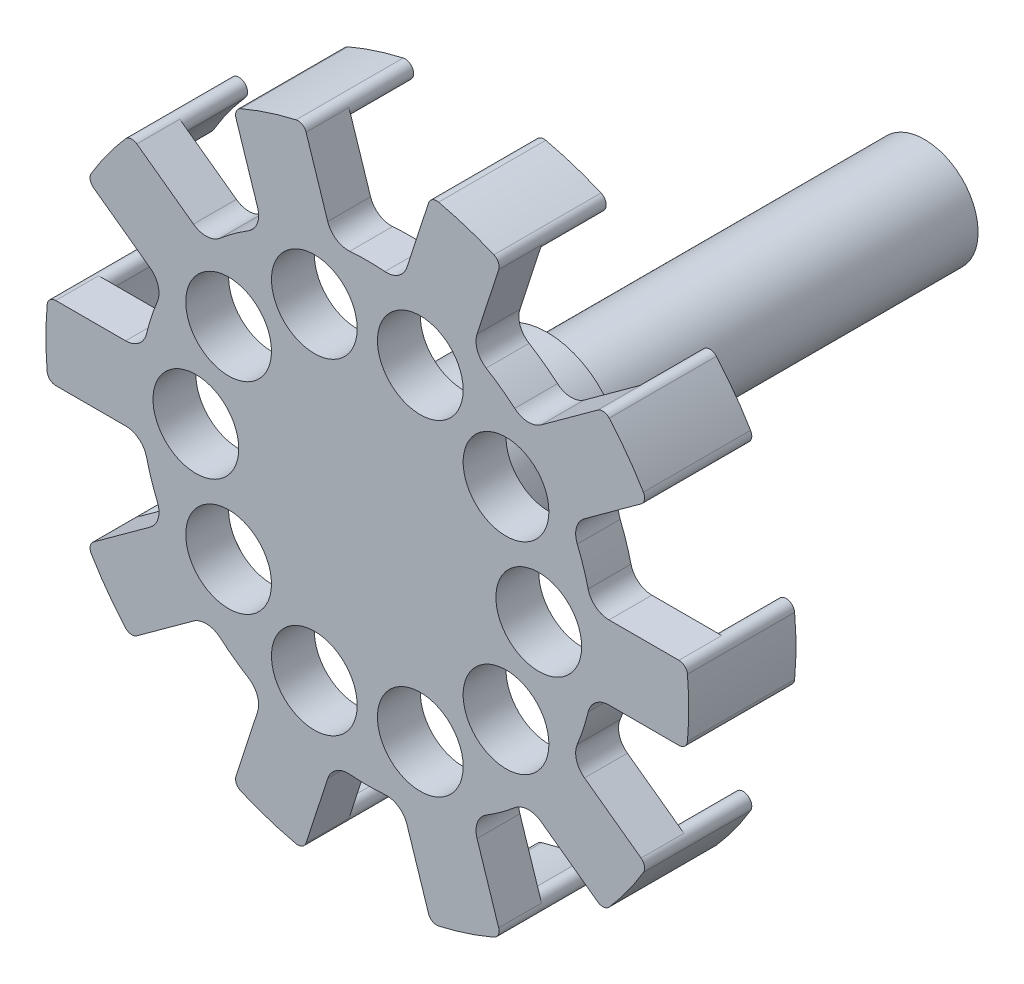
SolidWorks part; units mm, degrees
ref_plane "Piano frontale" through (0, 0, 0) normal (0, 0, 1) x (1, 0, 0)
ref_plane "Piano superiore" through (0, 0, 0) normal (0, 1, 0) x (1, 0, 0)
ref_plane "Piano destro" through (0, 0, 0) normal (1, 0, 0) x (0, 0, -1)
sketch "Schizzo1" plane through (0, 0, 0) normal (0, 0, 1) x (1, 0, 0)
  line L0 (-40, 0) -> (40, 0) construction
  circle A0 centre (0, 0) radius 53
  circle A1 centre (0, 0) radius 40 construction
  circle A2 centre (40, 0) radius 10
  circle A3 centre (0, 0) radius 40 construction
  circle A4 centre (32.3607, -23.5114) radius 10
  circle A5 centre (0, 0) radius 40 construction
  circle A6 centre (12.3607, -38.0423) radius 10
  circle A7 centre (0, 0) radius 40 construction
  circle A8 centre (-12.3607, -38.0423) radius 10
  circle A9 centre (0, 0) radius 40 construction
  circle A10 centre (-32.3607, -23.5114) radius 10
  circle A11 centre (0, 0) radius 40 construction
  circle A12 centre (-40, 0) radius 10
  circle A13 centre (0, 0) radius 40 construction
  circle A14 centre (-32.3607, 23.5114) radius 10
  circle A15 centre (0, 0) radius 40 construction
  circle A16 centre (-12.3607, 38.0423) radius 10
  circle A17 centre (0, 0) radius 40 construction
  circle A18 centre (12.3607, 38.0423) radius 10
  circle A19 centre (0, 0) radius 40 construction
  circle A20 centre (32.3607, 23.5114) radius 10
  dimension "D1" = 106
  dimension "D2" = 80
  dimension "D3" = 20
  dimension "D4" = 10
extrude "Estrusione-Estrusione1" add sketch "Schizzo1" along normal blind 10
sketch "Schizzo2" plane through (0, 0, 0) normal (0, 0, -1) x (-1, 0, 0)
  line L0 (0, 0) -> (117.2597, 0) construction
  line L1 (52.2976, 8.6) -> (72.701, 8.6)
  line L2 (52.2976, -8.6) -> (72.701, -8.6)
  line L3 (47.3646, -23.7822) -> (63.8713, -35.775)
  line L4 (37.2547, -37.6973) -> (53.7614, -49.6901)
  line L5 (24.3399, -47.0804) -> (30.6449, -66.4852)
  line L6 (7.9818, -52.3955) -> (14.2868, -71.8003)
  line L7 (-7.9818, -52.3955) -> (-14.2868, -71.8003)
  line L8 (-24.3399, -47.0804) -> (-30.6449, -66.4852)
  line L9 (-37.2547, -37.6973) -> (-53.7614, -49.6901)
  line L10 (-47.3646, -23.7822) -> (-63.8713, -35.775)
  line L11 (-52.2976, -8.6) -> (-72.701, -8.6)
  line L12 (-52.2976, 8.6) -> (-72.701, 8.6)
  line L13 (-47.3646, 23.7822) -> (-63.8713, 35.775)
  line L14 (-37.2547, 37.6973) -> (-53.7614, 49.6901)
  line L15 (-24.3399, 47.0804) -> (-30.6449, 66.4852)
  line L16 (-7.9818, 52.3955) -> (-14.2868, 71.8003)
  line L17 (7.9818, 52.3955) -> (14.2868, 71.8003)
  line L18 (24.3399, 47.0804) -> (30.6449, 66.4852)
  line L19 (37.2547, 37.6973) -> (53.7614, 49.6901)
  line L20 (47.3646, 23.7822) -> (63.8713, 35.775)
  circle A0 centre (0, 0) radius 53 construction
  arc A1 (64.4134, -38.4176) -> (56.4421, -49.3892) centre (0, 0) cw
  arc A2 (74.6928, 6.7808) -> (74.6928, -6.7808) centre (0, 0) cw
  arc A3 (74.6928, 6.7808) -> (72.701, 8.6) centre (72.701, 6.6) ccw
  arc A4 (74.6928, -6.7808) -> (72.701, -8.6) centre (72.701, -6.6) cw
  arc A5 (64.4134, -38.4176) -> (63.8713, -35.775) centre (62.6958, -37.3931) ccw
  arc A6 (56.4421, -49.3892) -> (53.7614, -49.6901) centre (54.937, -48.0721) cw
  arc A7 (29.5303, -68.9417) -> (16.6324, -73.1325) centre (0, 0) cw
  arc A8 (29.5303, -68.9417) -> (30.6449, -66.4852) centre (28.7428, -67.1033) ccw
  arc A9 (16.6324, -73.1325) -> (14.2868, -71.8003) centre (16.1889, -71.1823) cw
  arc A10 (-16.6324, -73.1325) -> (-29.5303, -68.9417) centre (0, 0) cw
  arc A11 (-16.6324, -73.1325) -> (-14.2868, -71.8003) centre (-16.1889, -71.1823) ccw
  arc A12 (-29.5303, -68.9417) -> (-30.6449, -66.4852) centre (-28.7428, -67.1033) cw
  arc A13 (-56.4421, -49.3892) -> (-64.4134, -38.4176) centre (0, 0) cw
  arc A14 (-56.4421, -49.3892) -> (-53.7614, -49.6901) centre (-54.937, -48.0721) ccw
  arc A15 (-64.4134, -38.4176) -> (-63.8713, -35.775) centre (-62.6958, -37.3931) cw
  arc A16 (-74.6928, -6.7808) -> (-74.6928, 6.7808) centre (0, 0) cw
  arc A17 (-74.6928, -6.7808) -> (-72.701, -8.6) centre (-72.701, -6.6) ccw
  arc A18 (-74.6928, 6.7808) -> (-72.701, 8.6) centre (-72.701, 6.6) cw
  arc A19 (-64.4134, 38.4176) -> (-56.4421, 49.3892) centre (0, 0) cw
  arc A20 (-64.4134, 38.4176) -> (-63.8713, 35.775) centre (-62.6958, 37.3931) ccw
  arc A21 (-56.4421, 49.3892) -> (-53.7614, 49.6901) centre (-54.937, 48.0721) cw
  arc A22 (-29.5303, 68.9417) -> (-16.6324, 73.1325) centre (0, 0) cw
  arc A23 (-29.5303, 68.9417) -> (-30.6449, 66.4852) centre (-28.7428, 67.1033) ccw
  arc A24 (-16.6324, 73.1325) -> (-14.2868, 71.8003) centre (-16.1889, 71.1823) cw
  arc A25 (16.6324, 73.1325) -> (29.5303, 68.9417) centre (0, 0) cw
  arc A26 (16.6324, 73.1325) -> (14.2868, 71.8003) centre (16.1889, 71.1823) ccw
  arc A27 (29.5303, 68.9417) -> (30.6449, 66.4852) centre (28.7428, 67.1033) cw
  arc A28 (56.4421, 49.3892) -> (64.4134, 38.4176) centre (0, 0) cw
  arc A29 (56.4421, 49.3892) -> (53.7614, 49.6901) centre (54.937, 48.0721) ccw
  arc A30 (64.4134, 38.4176) -> (63.8713, 35.775) centre (62.6958, 37.3931) cw
  arc A31 (-37.2547, 37.6973) -> (-47.3646, 23.7822) centre (0, 0) ccw
  arc A32 (-7.9818, 52.3955) -> (-24.3399, 47.0804) centre (0, 0) ccw
  arc A33 (24.3399, 47.0804) -> (7.9818, 52.3955) centre (0, 0) ccw
  arc A34 (47.3646, 23.7822) -> (37.2547, 37.6973) centre (0, 0) ccw
  arc A35 (52.2976, -8.6) -> (52.2976, 8.6) centre (0, 0) ccw
  arc A36 (37.2547, -37.6973) -> (47.3646, -23.7822) centre (0, 0) ccw
  arc A37 (7.9818, -52.3955) -> (24.3399, -47.0804) centre (0, 0) ccw
  arc A38 (-24.3399, -47.0804) -> (-7.9818, -52.3955) centre (0, 0) ccw
  arc A39 (-47.3646, -23.7822) -> (-37.2547, -37.6973) centre (0, 0) ccw
  arc A40 (-52.2976, 8.6) -> (-52.2976, -8.6) centre (0, 0) ccw
  dimension "D3" = 10
  dimension "D4" = 75
  dimension "D5" = 2
  dimension "D6" = 2
  dimension "D1" = 17.2
  dimension "D2" = 8.6
extrude "Estrusione-Estrusione2" add sketch "Schizzo2" against normal blind 10
sketch "Schizzo3" plane through (0, 0, 0) normal (0, 0, -1) x (-1, 0, 0)
  line L0 (72.701, 8.6) -> (52.2976, 8.6) construction
  line L1 (52.2976, -8.6) -> (72.701, -8.6) construction
  arc A0 (74.6928, -6.7808) -> (74.6928, 6.7808) centre (0, 0) ccw
  arc A1 (-56.4421, 49.3892) -> (-64.4134, 38.4176) centre (0, 0) ccw construction
  arc A2 (70.7092, -6.4192) -> (70.7092, 6.4192) centre (0, 0) ccw
  arc A3 (74.6928, 6.7808) -> (70.7092, 6.4192) centre (72.701, 6.6) ccw
  arc A4 (70.7092, -6.4192) -> (74.6928, -6.7808) centre (72.701, -6.6) ccw
  arc A5 (53.4319, -46.7551) -> (60.9781, -36.3686) centre (0, 0) ccw
  arc A6 (56.4421, -49.3892) -> (64.4134, -38.4176) centre (0, 0) ccw
  arc A7 (64.4134, -38.4176) -> (60.9781, -36.3686) centre (62.6958, -37.3931) ccw
  arc A8 (53.4319, -46.7551) -> (56.4421, -49.3892) centre (54.937, -48.0721) ccw
  arc A9 (15.7454, -69.2321) -> (27.9554, -65.2648) centre (0, 0) ccw
  arc A10 (16.6324, -73.1325) -> (29.5303, -68.9417) centre (0, 0) ccw
  arc A11 (29.5303, -68.9417) -> (27.9554, -65.2648) centre (28.7428, -67.1033) ccw
  arc A12 (15.7454, -69.2321) -> (16.6324, -73.1325) centre (16.1889, -71.1823) ccw
  arc A13 (-27.9554, -65.2648) -> (-15.7454, -69.2321) centre (0, 0) ccw
  arc A14 (-29.5303, -68.9417) -> (-16.6324, -73.1325) centre (0, 0) ccw
  arc A15 (-16.6324, -73.1325) -> (-15.7454, -69.2321) centre (-16.1889, -71.1823) ccw
  arc A16 (-27.9554, -65.2648) -> (-29.5303, -68.9417) centre (-28.7428, -67.1033) ccw
  arc A17 (-60.9781, -36.3686) -> (-53.4319, -46.7551) centre (0, 0) ccw
  arc A18 (-64.4134, -38.4176) -> (-56.4421, -49.3892) centre (0, 0) ccw
  arc A19 (-56.4421, -49.3892) -> (-53.4319, -46.7551) centre (-54.937, -48.0721) ccw
  arc A20 (-60.9781, -36.3686) -> (-64.4134, -38.4176) centre (-62.6958, -37.3931) ccw
  arc A21 (-70.7092, 6.4192) -> (-70.7092, -6.4192) centre (0, 0) ccw
  arc A22 (-74.6928, 6.7808) -> (-74.6928, -6.7808) centre (0, 0) ccw
  arc A23 (-74.6928, -6.7808) -> (-70.7092, -6.4192) centre (-72.701, -6.6) ccw
  arc A24 (-70.7092, 6.4192) -> (-74.6928, 6.7808) centre (-72.701, 6.6) ccw
  arc A25 (-53.4319, 46.7551) -> (-60.9781, 36.3686) centre (0, 0) ccw
  arc A26 (-56.4421, 49.3892) -> (-64.4134, 38.4176) centre (0, 0) ccw
  arc A27 (-64.4134, 38.4176) -> (-60.9781, 36.3686) centre (-62.6958, 37.3931) ccw
  arc A28 (-53.4319, 46.7551) -> (-56.4421, 49.3892) centre (-54.937, 48.0721) ccw
  arc A29 (-15.7454, 69.2321) -> (-27.9554, 65.2648) centre (0, 0) ccw
  arc A30 (-16.6324, 73.1325) -> (-29.5303, 68.9417) centre (0, 0) ccw
  arc A31 (-29.5303, 68.9417) -> (-27.9554, 65.2648) centre (-28.7428, 67.1033) ccw
  arc A32 (-15.7454, 69.2321) -> (-16.6324, 73.1325) centre (-16.1889, 71.1823) ccw
  arc A33 (27.9554, 65.2648) -> (15.7454, 69.2321) centre (0, 0) ccw
  arc A34 (29.5303, 68.9417) -> (16.6324, 73.1325) centre (0, 0) ccw
  arc A35 (16.6324, 73.1325) -> (15.7454, 69.2321) centre (16.1889, 71.1823) ccw
  arc A36 (27.9554, 65.2648) -> (29.5303, 68.9417) centre (28.7428, 67.1033) ccw
  arc A37 (60.9781, 36.3686) -> (53.4319, 46.7551) centre (0, 0) ccw
  arc A38 (64.4134, 38.4176) -> (56.4421, 49.3892) centre (0, 0) ccw
  arc A39 (56.4421, 49.3892) -> (53.4319, 46.7551) centre (54.937, 48.0721) ccw
  arc A40 (60.9781, 36.3686) -> (64.4134, 38.4176) centre (62.6958, 37.3931) ccw
  dimension "D1" = 142
  dimension "D2" = 10
extrude "Estrusione-Estrusione3" add sketch "Schizzo3" along normal blind 15
fillet "Raccordo1" radius 5 20 edges at (7.9818, 52.3955, 5) (24.3399, 47.0804, 5) (-7.9818, 52.3955, 5) (-37.2547, 37.6973, 5) (-24.3399, 47.0804, 5) (-47.3646, -23.7822, 5) (-52.2976, 8.6, 5) (-47.3646, 23.7822, 5) (-52.2976, -8.6, 5) (-7.9818, -52.3955, 5) (-24.3399, -47.0804, 5) (-37.2547, -37.6973, 5) (7.9818, -52.3955, 5) (37.2547, -37.6973, 5) (24.3399, -47.0804, 5) (52.2976, -8.6, 5) (47.3646, -23.7822, 5) (52.2976, 8.6, 5) (47.3646, 23.7822, 5) (37.2547, 37.6973, 5)
sketch "Schizzo4" plane through (0, 0, 0) normal (0, 0, -1) x (-1, 0, 0)
  circle A0 centre (0, 0) radius 17.5
  dimension "D1" = 35
extrude "Estrusione-Estrusione4" add sketch "Schizzo4" along normal blind 32
sketch "Schizzo5" plane through (0, 0, -32) normal (0, 0, -1) x (-1, 0, 0)
  circle A0 centre (0, 0) radius 12.5
  dimension "D1" = 25
extrude "Estrusione-Estrusione5" add sketch "Schizzo5" along normal blind 88
